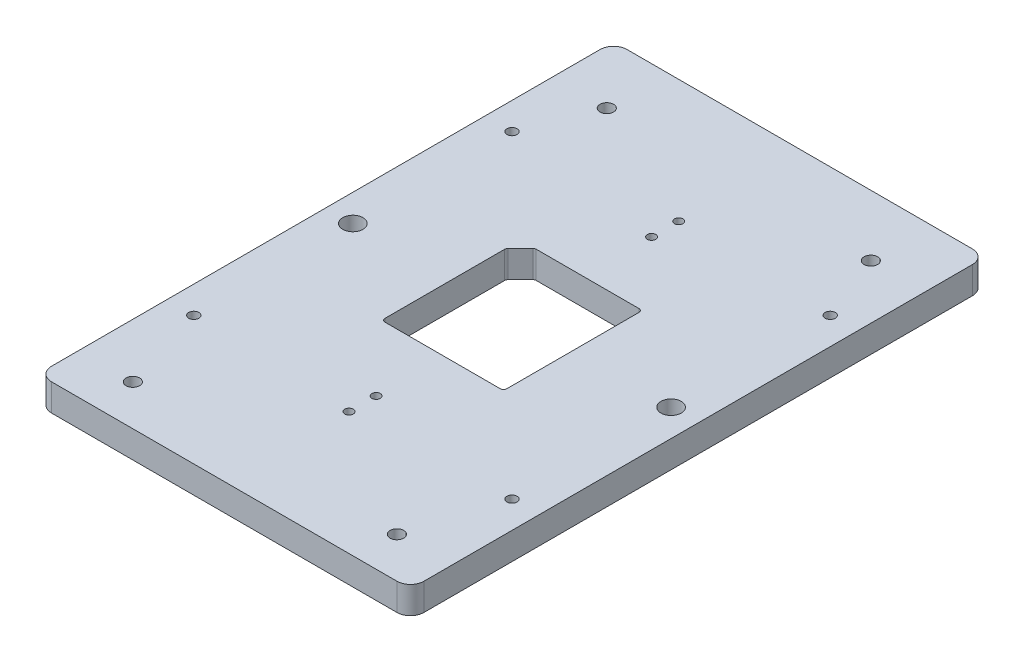
SolidWorks part; units mm, degrees
ref_plane "Alzado" through (0, 0, 0) normal (0, 0, 1) x (1, 0, 0)
ref_plane "Planta" through (0, 0, 0) normal (0, 1, 0) x (1, 0, 0)
ref_plane "Vista lateral" through (0, 0, 0) normal (1, 0, 0) x (0, 0, -1)
sketch "Croquis1" plane through (0, 0, 0) normal (0, 1, 0) x (1, 0, 0)
  line L1 (-51, 85) -> (51, 85)
  line L2 (-55, 81) -> (-55, -81)
  line L3 (-51, -85) -> (51, -85)
  line L4 (55, 81) -> (55, -81)
  line L5 (-55, 85) -> (55, -85) construction
  line L6 (-55, -85) -> (55, 85) construction
  arc A0 (-55, -81) -> (-51, -85) centre (-51, -81) ccw
  arc A1 (51, -85) -> (55, -81) centre (51, -81) ccw
  arc A2 (51, 85) -> (55, 81) centre (51, 81) cw
  arc A3 (-51, 85) -> (-55, 81) centre (-51, 81) ccw
  point P0 (0, 0)
  dimension "D3" = 4
  dimension "D1" = 110
  dimension "D2" = 170
extrude "Saliente-Extruir1" add sketch "Croquis1" along normal blind 8
sketch "Croquis2" plane through (0, 8, 0) normal (0, 1, 0) x (1, 0, 0)
  line L0 (51, 85) -> (-51, 85) construction
  line L1 (-55, 81) -> (-55, -81) construction
  line L2 (0, 0) -> (32.1347, 0) construction
  line L3 (32.1347, 0) -> (0, 33.1012) construction
  line L4 (0, 33.1012) -> (0, 0) construction
  circle A0 centre (-39, 73) radius 2
  circle A1 centre (-47, 47) radius 1.5
  circle A2 centre (47, 47) radius 1.5
  circle A3 centre (39, 73) radius 2
  circle A4 centre (39, -73) radius 2
  circle A5 centre (47, -47) radius 1.5
  circle A6 centre (-47, -47) radius 1.5
  circle A7 centre (-39, -73) radius 2
  circle A8 centre (-47, 0) radius 3
  circle A9 centre (47, 0) radius 3
  dimension "D5" = 3
  dimension "D6" = 4
  dimension "D7" = 6
  dimension "D8" = 6
  dimension "D1" = 12
  dimension "D2" = 16
  dimension "D3" = 38
  dimension "D4" = 8
extrude "Cortar-Extruir1" cut sketch "Croquis2" against normal blind 18
sketch "Croquis3" plane through (0, 8, 0) normal (0, 1, 0) x (1, 0, 0)
  line L1 (18, 20.5) -> (-18, 20.5)
  line L2 (18, 20.5) -> (18, -20.5)
  line L3 (18, -20.5) -> (-18, -20.5)
  line L4 (-18, 20.5) -> (-18, -20.5)
extrude "Cortar-Extruir2" cut sketch "Croquis3" against normal up to surface (8 mm away) up to face at (47, 0, 48.5)
sketch "Croquis4" plane through (0, 0, 0) normal (0, -1, 0) x (1, 0, 0)
  line L1 (-25, 45) -> (25, 45)
  line L2 (-25, 45) -> (-25, -45)
  line L3 (-25, -45) -> (25, -45)
  line L4 (25, 45) -> (25, -45)
  line L5 (-25, 45) -> (25, -45) construction
  line L6 (-25, -45) -> (25, 45) construction
  point P0 (0, 0)
  dimension "D1" = 50
  dimension "D2" = 90
extrude "Cortar-Extruir3" cut sketch "Croquis4" against normal up to surface (8 mm away) up to face at (0, 8, 0)
sketch "Croquis5" plane through (0, 0, 0) normal (0, -1, 0) x (1, 0, 0)
  line L5 (-13.3431, -20.5) -> (17, -20.5) construction
  line L6 (-29.3851, 50.8307) -> (30.546, 50.8307)
  line L7 (-29.3851, 50.8307) -> (-29.3851, -49.7355)
  line L8 (-29.3851, -49.7355) -> (30.546, -49.7355)
  line L9 (30.546, 50.8307) -> (30.546, -49.7355)
  line L10 (-17.7071, -16.5503) -> (-14.0503, -20.2071) construction
  line L11 (-18, 19.5) -> (-18, -15.8431) construction
  line L12 (17, 20.5) -> (-17, 20.5) construction
  line L13 (18, -19.5) -> (18, 19.5) construction
  line L14 (-13.3431, -20.5) -> (17, -20.5)
  line L15 (-17.7071, -16.5503) -> (-14.0503, -20.2071)
  line L16 (-18, 19.5) -> (-18, -15.8431)
  line L17 (17, 20.5) -> (-17, 20.5)
  line L18 (18, -19.5) -> (18, 19.5)
  arc A5 (17, -20.5) -> (18, -19.5) centre (17, -19.5) ccw construction
  arc A6 (-14.0503, -20.2071) -> (-13.3431, -20.5) centre (-13.3431, -19.5) ccw construction
  arc A7 (-18, -15.8431) -> (-17.7071, -16.5503) centre (-17, -15.8431) ccw construction
  arc A8 (-17, 20.5) -> (-18, 19.5) centre (-17, 19.5) ccw construction
  arc A9 (18, 19.5) -> (17, 20.5) centre (17, 19.5) ccw construction
  arc A10 (17, -20.5) -> (18, -19.5) centre (17, -19.5) ccw
  arc A11 (-14.0503, -20.2071) -> (-13.3431, -20.5) centre (-13.3431, -19.5) ccw
  arc A12 (-18, -15.8431) -> (-17.7071, -16.5503) centre (-17, -15.8431) ccw
  arc A13 (-17, 20.5) -> (-18, 19.5) centre (-17, 19.5) ccw
  arc A14 (18, 19.5) -> (17, 20.5) centre (17, 19.5) ccw
extrude "Saliente-Extruir2" add sketch "Croquis5" against normal up to surface (8 mm away) up to face at (0, 8, 0)
sketch "Croquis7" plane through (0, 8, 0) normal (0, 1, 0) x (1, 0, 0)
  line L1 (-45.9498, 76.3096) -> (48.3234, 76.3096)
  line L2 (-45.9498, 76.3096) -> (-45.9498, 67.6728)
  line L3 (-45.9498, 67.6728) -> (48.3234, 67.6728)
  line L4 (48.3234, 76.3096) -> (48.3234, 67.6728)
extrude "Saliente-Extruir3" add sketch "Croquis7" against normal up to surface (8 mm away) up to face at (47, 0, 48.5)
sketch "Croquis8" plane through (0, 8, 0) normal (0, 1, 0) x (1, 0, 0)
  line L0 (-39, -75) -> (-39, 67) construction
  line L2 (39, 67) -> (39, -73) construction
  line L3 (51, 85) -> (-51, 85) construction
  circle A0 centre (-39, -73) radius 2 construction
  circle A1 centre (-39, 67) radius 2
  circle A2 centre (39, 67) radius 2
  dimension "D3" = 4
  dimension "D4" = 4
  dimension "D1" = 18
  dimension "D2" = 18
extrude "Cortar-Extruir4" cut sketch "Croquis8" against normal through all
sketch "Croquis9" plane through (0, 0, 0) normal (0, -1, 0) x (1, 0, 0)
  line L0 (18, 0) -> (27, 0) construction
  line L1 (18, -19.5) -> (18, 19.5) construction
  circle A0 centre (0.5477, 40.687) radius 1.25
  circle A1 centre (0.5477, 48.687) radius 1.25
  circle A2 centre (0.5477, -48.687) radius 1.25
  circle A3 centre (0.5477, -40.687) radius 1.25
  dimension "D1" = 2.5
  dimension "D2" = 2.5
extrude "Cortar-Extruir5" cut sketch "Croquis9" against normal up to surface (8 mm away) up to face at (39, 8, -65)
ref_plane "Plano1" through (0, 0, 0) normal (1, 0, 0) x (0, 0, -1)
